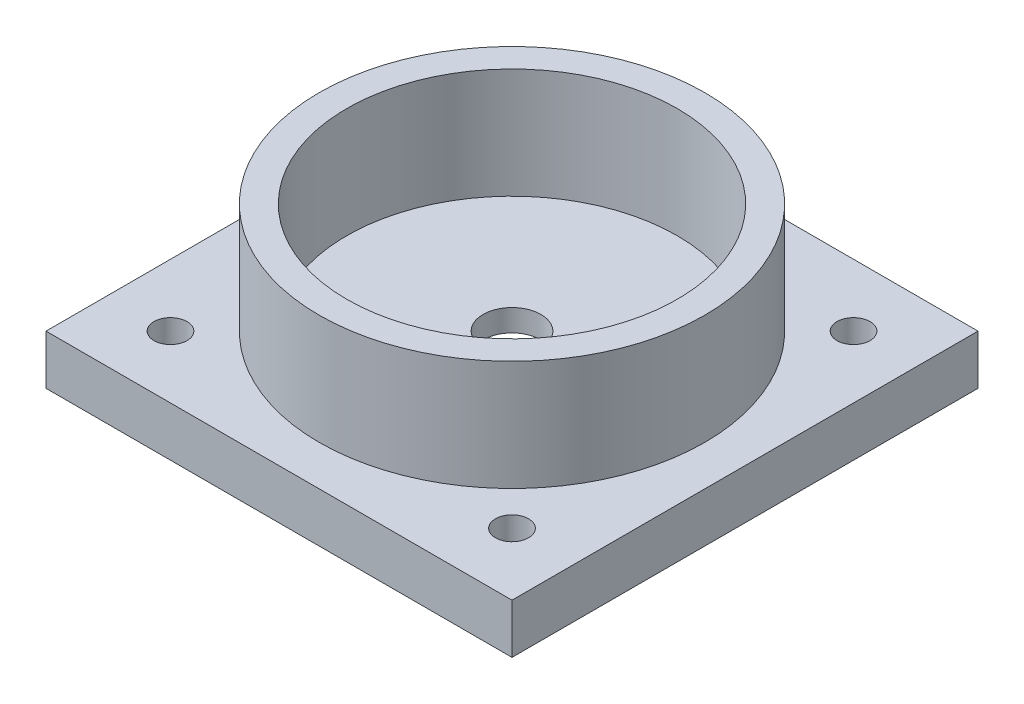
SolidWorks part; units mm, degrees
ref_plane "Front Plane" through (0, 0, 0) normal (0, 0, 1) x (1, 0, 0)
ref_plane "Top Plane" through (0, 0, 0) normal (0, 1, 0) x (1, 0, 0)
ref_plane "Right Plane" through (0, 0, 0) normal (1, 0, 0) x (0, 0, -1)
sketch "Sketch1" plane through (0, 0, 0) normal (0, 1, 0) x (1, 0, 0)
  line L1 (-21.15, -21.15) -> (21.15, -21.15)
  line L2 (-21.15, -21.15) -> (-21.15, 21.15)
  line L3 (-21.15, 21.15) -> (21.15, 21.15)
  line L4 (21.15, -21.15) -> (21.15, 21.15)
  line L5 (-21.15, -21.15) -> (21.15, 21.15) construction
  line L6 (-21.15, 21.15) -> (21.15, -21.15) construction
  circle A0 centre (-15.5, 15.5) radius 1.5
  circle A1 centre (15.5, 15.5) radius 1.5
  circle A2 centre (-15.5, -15.5) radius 1.5
  circle A3 centre (15.5, -15.5) radius 1.5
  point P0 (0, 0)
  point P14 (0, 0)
  point P15 (0, 0)
  point P16 (-15.5184, 15.6886)
  point P17 (0, 0)
  point P18 (0, 0)
  point P19 (0, 0)
  point P20 (0, 0)
  dimension "D2" = 3
  dimension "D1" = 42.3
  dimension "D3" = 31
  dimension "D4" = 31
  dimension "D5" = 15.5
  dimension "D6" = 15.5
extrude "Boss-Extrude1" add sketch "Sketch1" along normal blind 4.5
sketch "Sketch2" plane through (0, 0, 0) normal (0, -1, 0) x (1, 0, 0)
  circle A0 centre (0, 0) radius 11
  dimension "D1" = 22
extrude "Cut-Extrude1" cut sketch "Sketch2" against normal blind 2.5
sketch "Sketch3" plane through (0, 2.5, 0) normal (0, -1, 0) x (1, 0, 0)
  circle A0 centre (0, 0) radius 2.625
  dimension "D1" = 5.25
extrude "Cut-Extrude2" cut sketch "Sketch3" against normal up to surface (2 mm away) contours A0 up to face at (0, 4.5, 0)
sketch "Sketch4" plane through (0, 4.5, 0) normal (0, 1, 0) x (1, 0, 0)
  circle A0 centre (0, 0) radius 17.5
  circle A3 centre (0, 0) radius 15
  dimension "D1" = 35
  dimension "D2" = 30
extrude "Boss-Extrude2" add sketch "Sketch4" along normal blind 10
